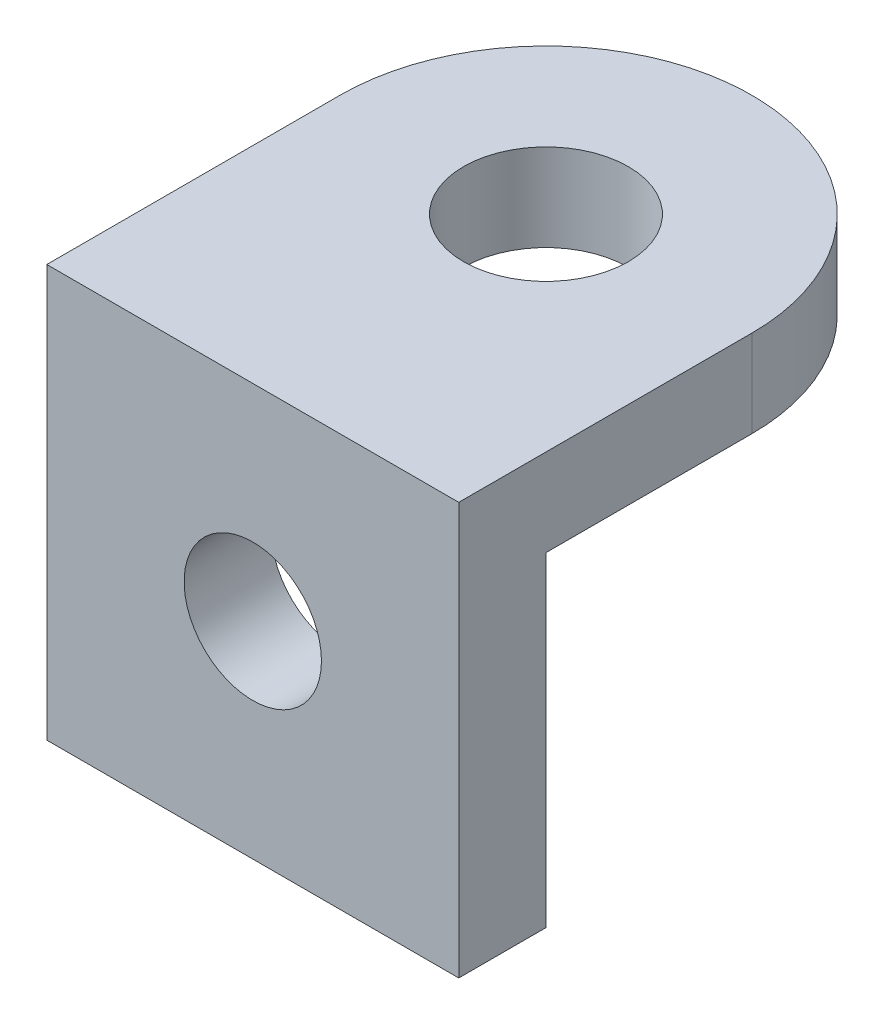
SolidWorks part; units mm, degrees
ref_plane "Front Plane" through (0, 0, 0) normal (0, 0, 1) x (1, 0, 0)
ref_plane "Top Plane" through (0, 0, 0) normal (0, 1, 0) x (1, 0, 0)
ref_plane "Right Plane" through (0, 0, 0) normal (1, 0, 0) x (0, 0, -1)
sketch "Sketch1" plane through (0, 0, 0) normal (0, 0, 1) x (1, 0, 0)
  line L1 (-7.5, 0) -> (7.5, 0)
  line L2 (-7.5, 0) -> (-7.5, -15)
  line L3 (-7.5, -15) -> (7.5, -15)
  line L4 (7.5, 0) -> (7.5, -15)
  line L5 (-7.5, 0) -> (7.5, -15) construction
  line L6 (-7.5, -15) -> (7.5, 0) construction
  circle A0 centre (0, -7.5) radius 2.5
  point P0 (0, -7.5)
  dimension "D3" = 5
  dimension "D1" = 15
  dimension "D2" = 15
extrude "Boss-Extrude1" add sketch "Sketch1" along normal blind 3.175
sketch "Sketch2" plane through (0, 0, 0) normal (0, 1, 0) x (1, 0, 0)
  line L0 (7.5, 0) -> (-7.5, 0) construction
  line L2 (-7.5, 7.5) -> (-7.5, 0)
  line L3 (-7.5, 0) -> (7.5, 0)
  line L4 (7.5, 7.5) -> (7.5, 0)
  line L5 (-7.5, 15) -> (7.5, 0) construction
  line L6 (-7.5, 0) -> (7.5, 15) construction
  line L7 (-7.5, 7.5) -> (-7.5, 15) construction
  line L8 (-7.5, 15) -> (7.5, 15) construction
  line L9 (7.5, 15) -> (7.5, 7.5) construction
  circle A0 centre (0, 7.5) radius 3
  arc A2 (7.5, 7.5) -> (-7.5, 7.5) centre (0, 7.5) ccw
  point P0 (0, 7.5)
  dimension "D2" = 6
  dimension "D1" = 15
extrude "Boss-Extrude2" add sketch "Sketch2" against normal blind 3.175
